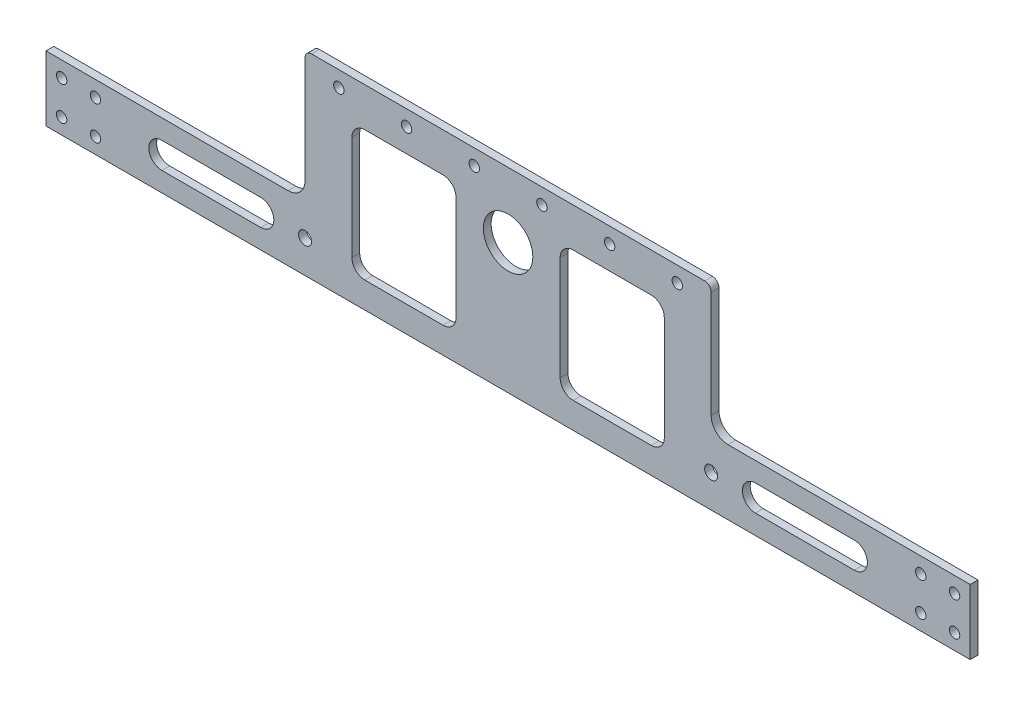
SolidWorks part; units mm, degrees
material "Alumina"
ref_plane "Front Plane" through (0, 0, 0) normal (0, 0, 1) x (1, 0, 0)
ref_plane "Top Plane" through (0, 0, 0) normal (0, 1, 0) x (1, 0, 0)
ref_plane "Right Plane" through (0, 0, 0) normal (1, 0, 0) x (0, 0, -1)
sketch "Sketch1" plane through (0, 0, 0) normal (0, 0, 1) x (1, 0, 0)
  line L0 (0, 0) -> (0, 50000) construction
  line L1 (0, 0) -> (50000, 0) construction
  line L4 (177.5, 0) -> (177.5, 25)
  line L5 (177.5, 25) -> (84.5, 25)
  line L6 (78, 31.5) -> (78, 72.5)
  line L7 (75.5, 75) -> (-75.5, 75)
  line L8 (-78, 72.5) -> (-78, 31.5)
  line L9 (-84.5, 25) -> (-177.5, 25)
  line L10 (-177.5, 25) -> (-177.5, 0)
  line L11 (-177.5, 0) -> (177.5, 0)
  line L12 (-65, 69) -> (-39, 69) construction
  line L13 (-177.5, 12.5) -> (177.5, 12.5) construction
  line L14 (-55, 60) -> (-25, 60)
  line L15 (-60, 55) -> (-60, 15)
  line L16 (-55, 10) -> (-25, 10)
  line L17 (-20, 55) -> (-20, 15)
  line L18 (-133, 12.5) -> (-95, 12.5) construction
  line L19 (-133, 17.5) -> (-95, 17.5)
  line L20 (-133, 7.5) -> (-95, 7.5)
  line L21 (133, 12.5) -> (95, 12.5) construction
  line L22 (133, 17.5) -> (95, 17.5)
  line L23 (133, 7.5) -> (95, 7.5)
  line L24 (55, 10) -> (25, 10)
  line L25 (20, 55) -> (20, 15)
  line L26 (55, 60) -> (25, 60)
  line L27 (60, 55) -> (60, 15)
  arc A0 (-84.5, 25) -> (-78, 31.5) centre (-84.5, 31.5) ccw
  arc A1 (78, 31.5) -> (84.5, 25) centre (84.5, 31.5) ccw
  circle A2 centre (0, 50) radius 9.5
  arc A3 (78, 72.5) -> (75.5, 75) centre (75.5, 72.5) ccw
  arc A4 (-75.5, 75) -> (-78, 72.5) centre (-75.5, 72.5) ccw
  circle A5 centre (-65, 69) radius 2
  circle A6 centre (-39, 69) radius 2
  circle A7 centre (-13, 69) radius 2
  circle A8 centre (13, 69) radius 2
  circle A9 centre (39, 69) radius 2
  circle A10 centre (65, 69) radius 2
  circle A11 centre (-78, 12.5) radius 2.5
  arc A12 (-55, 60) -> (-60, 55) centre (-55, 55) ccw
  arc A13 (-25, 60) -> (-20, 55) centre (-25, 55) cw
  arc A14 (-25, 10) -> (-20, 15) centre (-25, 15) ccw
  arc A15 (-60, 15) -> (-55, 10) centre (-55, 15) ccw
  arc A16 (-133, 17.5) -> (-133, 7.5) centre (-133, 12.5) ccw
  arc A17 (-95, 7.5) -> (-95, 17.5) centre (-95, 12.5) ccw
  circle A18 centre (-171.5, 19) radius 2
  circle A19 centre (-158.5, 19) radius 2
  circle A20 centre (-171.5, 6) radius 2
  circle A21 centre (-158.5, 6) radius 2
  circle A22 centre (171.5, 6) radius 2
  circle A23 centre (171.5, 19) radius 2
  circle A24 centre (158.5, 19) radius 2
  circle A25 centre (158.5, 6) radius 2
  arc A26 (133, 17.5) -> (133, 7.5) centre (133, 12.5) cw
  arc A27 (95, 7.5) -> (95, 17.5) centre (95, 12.5) cw
  circle A28 centre (78, 12.5) radius 2.5
  arc A29 (25, 10) -> (20, 15) centre (25, 15) cw
  arc A30 (25, 60) -> (20, 55) centre (25, 55) ccw
  arc A31 (55, 60) -> (60, 55) centre (55, 55) cw
  arc A32 (60, 15) -> (55, 10) centre (55, 15) cw
  point P10 (0, 75)
  point P15 (0, 0)
  point P23 (78, 75)
  point P26 (-78, 75)
  point P59 (-114, 12.5)
  point P72 (0, 0)
  point P73 (0, 0)
  point P74 (0, 0)
  point P75 (0, 0)
  point P86 (114, 12.5)
  dimension "D4" = 13
  dimension "D5" = 19
  dimension "D7" = 2.5
  dimension "D8" = 4
  dimension "D18" = 5
  dimension "D19" = 5
  dimension "D1" = 50
  dimension "156" = 156
  dimension "D2" = 25
  dimension "D3" = 355
  dimension "D6" = 50
  dimension "D9" = 6
  dimension "D10" = 13
  dimension "D12" = 26
  dimension "D13" = 50
  dimension "D14" = 10
  dimension "D15" = 40
  dimension "D16" = 20
  dimension "D17" = 18
  dimension "D20" = 10
  dimension "D21" = 38
  dimension "D22" = 17
  dimension "D23" = 13
  dimension "D24" = 13
  dimension "D25" = 6
  dimension "D26" = 6
  dimension "D11" = 6
extrude "Boss-Extrude1" add sketch "Sketch1" along normal mid plane 3 contours L7 A4 L8 A0 L9 L10 L11 L4 L5 A1 L6 A3 L23 A27 L22 A26 A25 A23 A2 A5 A6 A7 A8 A9 A10 A11 A15 L15 A12 L14 A13 L17 A14 L16 A17 L20 A16 L19
